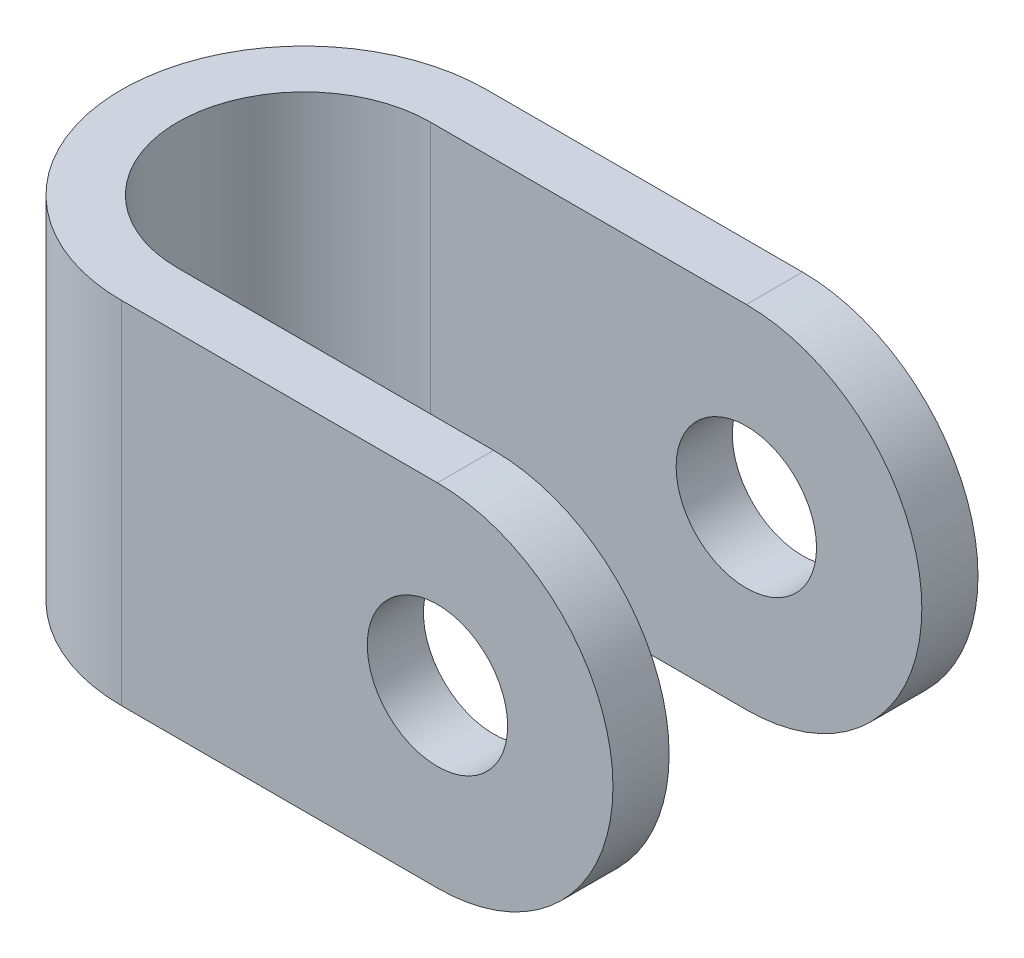
SolidWorks part; units mm, degrees
ref_plane "Front Plane" through (0, 0, 0) normal (0, 0, 1) x (1, 0, 0)
ref_plane "Top Plane" through (0, 0, 0) normal (0, 1, 0) x (1, 0, 0)
ref_plane "Right Plane" through (0, 0, 0) normal (1, 0, 0) x (0, 0, -1)
sketch "Sketch1" plane through (0, 0, 0) normal (0, 1, 0) x (1, 0, 0)
  line L0 (-48.5868, 0) -> (58.3694, 0) construction
  line L1 (0, 13) -> (35, 13)
  line L2 (0, 9) -> (35, 9)
  line L3 (35, 13) -> (35, 9)
  line L4 (0, -13) -> (35, -13)
  line L5 (35, -13) -> (35, -9)
  line L6 (0, -9) -> (35, -9)
  arc A0 (-13, 0) -> (0, 13) centre (0, 0) cw
  arc A1 (-9, 0) -> (0, 9) centre (0, 0) cw
  arc A2 (-13, 0) -> (0, -13) centre (0, 0) ccw
  arc A3 (-9, 0) -> (0, -9) centre (0, 0) ccw
  dimension "D2" = 18
  dimension "D3" = 35
  dimension "D1" = 4
extrude "Boss-Extrude1" add sketch "Sketch1" along normal mid plane 25
sketch "Sketch2" plane through (0, 0, 13) normal (0, 0, 1) x (1, 0, 0)
  line L0 (0, 0) -> (38.0766, 0) construction
  line L1 (0, 12.5) -> (0, -12.5) construction
  line L2 (0, 12.5) -> (35, 12.5) construction
  line L3 (35, 12.5) -> (35, -12.5) construction
  circle A0 centre (22.5, 0) radius 5
  arc A1 (22.5, 12.5) -> (22.5, -12.5) centre (22.5, 0) cw
  line M1 (0, -12.5) -> (35, -12.5)
  line M2 (35, -12.5) -> (35, 12.5)
  line M3 (35, 12.5) -> (0, 12.5)
  dimension "D1" = 10
extrude "Cut-Extrude1" cut sketch "Sketch2" against normal through all contours L0 A0 | A0 L0 | A1 M3 M2 | A1 M2 M1
